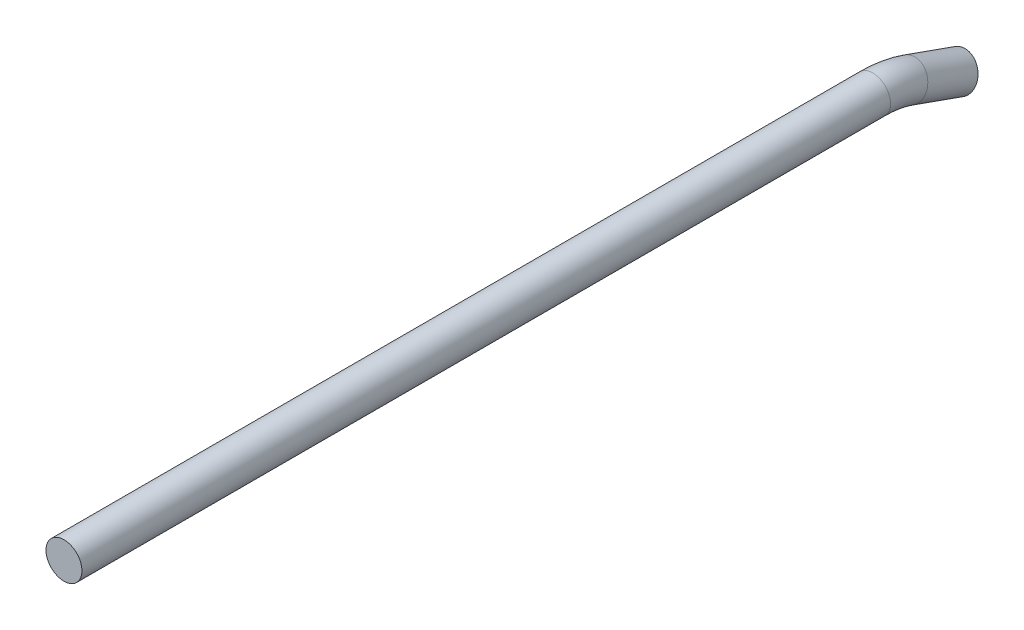
SolidWorks part; units mm, degrees
ref_plane "Front Plane" through (0, 0, 0) normal (0, 0, 1) x (1, 0, 0)
ref_plane "Top Plane" through (0, 0, 0) normal (0, 1, 0) x (1, 0, 0)
ref_plane "Right Plane" through (0, 0, 0) normal (1, 0, 0) x (0, 0, -1)
sketch "Sketch1" plane through (0, 0, 0) normal (0, 0, 1) x (1, 0, 0)
  circle A0 centre (0, 0) radius 0.5
  dimension "D1" = 1
sketch "Sketch2" plane through (0, 0, 0) normal (1, 0, 0) x (0, 0, -1)
  line L0 (0, 0) -> (22.4818, 0)
  line L1 (23.4882, -0.1738) -> (24.8841, -0.6709)
  arc A0 (22.4818, 0) -> (23.4882, -0.1738) centre (22.4818, -3) cw
  point P6 (23, 0)
  dimension "D4" = 3
  dimension "D1" = 23
  dimension "D2" = 2
  dimension "D3" = 19.6
sweep "Sweep1" add profiles "Sketch1" path "Sketch2"
